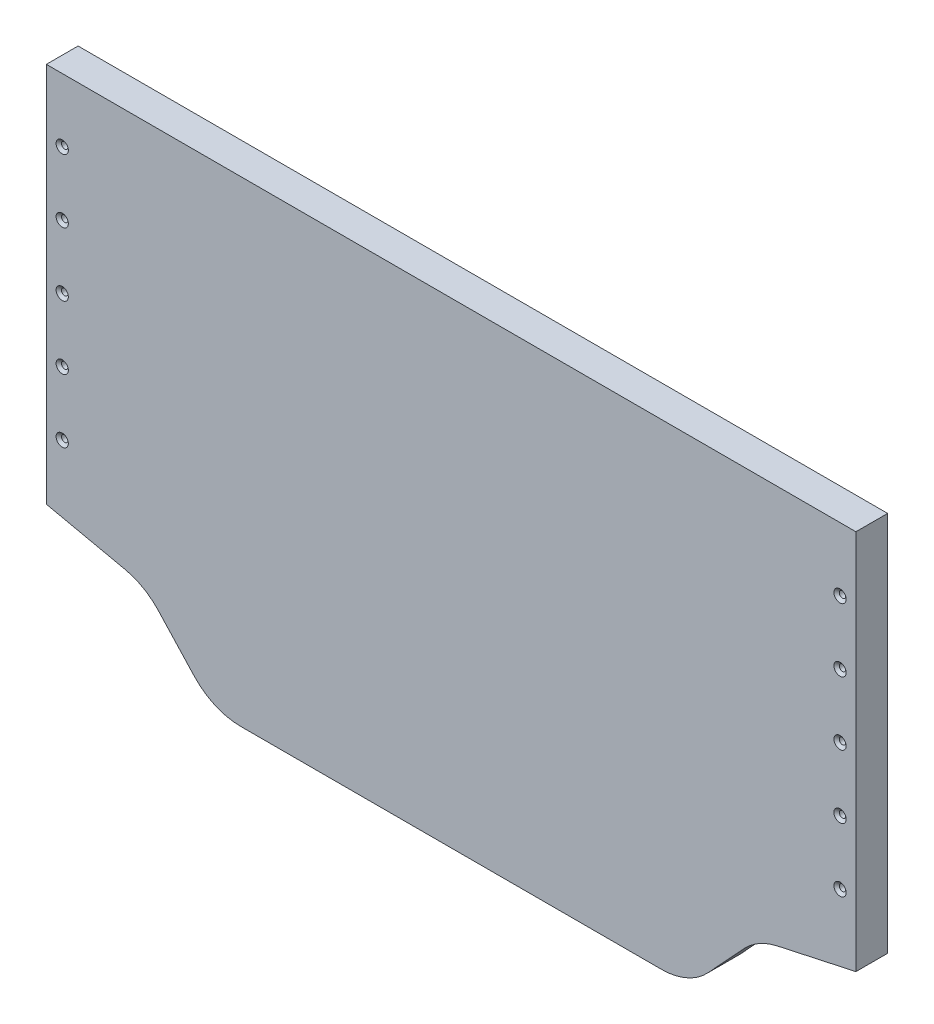
SolidWorks part; units mm, degrees
ref_plane "Front Plane" through (0, 0, 0) normal (0, 0, 1) x (1, 0, 0)
ref_plane "Top Plane" through (0, 0, 0) normal (0, 1, 0) x (1, 0, 0)
ref_plane "Right Plane" through (0, 0, 0) normal (1, 0, 0) x (0, 0, -1)
sketch "Sketch1" plane through (0, 0, 0) normal (0, 0, 1) x (1, 0, 0)
  line L0 (-245.1621, 59.1225) -> (-190.5, 0)
  line L2 (323.85, 76.2) -> (323.85, 381)
  line L3 (323.85, 381) -> (-323.85, 381)
  line L4 (-323.85, 76.2) -> (-323.85, 381)
  line L5 (-190.5, 0) -> (190.5, 0)
  line L7 (0, 0) -> (0, 381) construction
  line L8 (-245.1621, 59.1225) -> (-323.85, 76.2)
  line L9 (245.1621, 59.1225) -> (190.5, 0)
  line L10 (245.1621, 59.1225) -> (323.85, 76.2)
  dimension "D1" = 381
  dimension "D2" = 76.2
  dimension "D3" = 647.7
  dimension "D4" = 304.8
  dimension "D6" = 145
extrude "Boss-Extrude1" add sketch "Sketch1" along normal blind 25.4
fillet "Fillet1" radius 50.8 4 edges at (-190.5, 0, 12.7) (-245.1621, 59.1225, 12.7) (245.1621, 59.1225, 12.7) (190.5, 0, 12.7)
hole_wizard "CSK for #10 Flat Head Machine Screw (100)1" positions "Sketch2" profile "Sketch4" countersink size "#10" standard "ANSI Inch"
sketch "Sketch2" plane through (298.45, 0, 25.4) normal (0, 0, -1) x (-1, 0, 0)
  line L0 (-12.7, 381) -> (-12.7, 330.2) construction
  line L3 (-25.4, 381) -> (622.3, 381) construction
  line L4 (-25.4, 76.2) -> (-25.4, 381) construction
  point P0 (-12.7, 330.2)
  point P22 (-12.7, 279.4)
  point P23 (-12.7, 228.6)
  point P24 (-12.7, 177.8)
  point P25 (-12.7, 127)
  dimension "D1" = 5
  dimension "D2" = 50.8
  dimension "D3" = 12.7
  dimension "D4" = 50.8
sketch "Sketch4" plane through (311.15, 330.2, 25.4) normal (1, 0, 0) x (0, -1, 0)
  line L0 (0, 0) -> (0, 52.3338)
  line L1 (0, 52.3338) -> (2.5527, 50.8)
  line L2 (2.5527, 50.8) -> (2.5527, 1.9608)
  line L3 (2.5527, 1.9608) -> (4.8895, 0)
  line L5 (4.8895, 0) -> (0, 0)
  line L6 (-2.5527, 1.9608) -> (-4.8895, 0) construction
  line L10 (0, 52.3338) -> (-2.5527, 50.8) construction
  line L11 (0, -6.35) -> (0, 107.95) construction
  dimension "Hole Dia." = 5.1054
  dimension "Hole Depth" = 50.8
  dimension "Near C'Sink Dia." = 9.779
  dimension "Near C'Sink Angle" = 100
  dimension "Drill Angle" = 118
mirror "Mirror1" about plane through (0, 0, 0) normal (1, 0, 0) of "CSK for #10 Flat Head Machine Screw (100)1"
